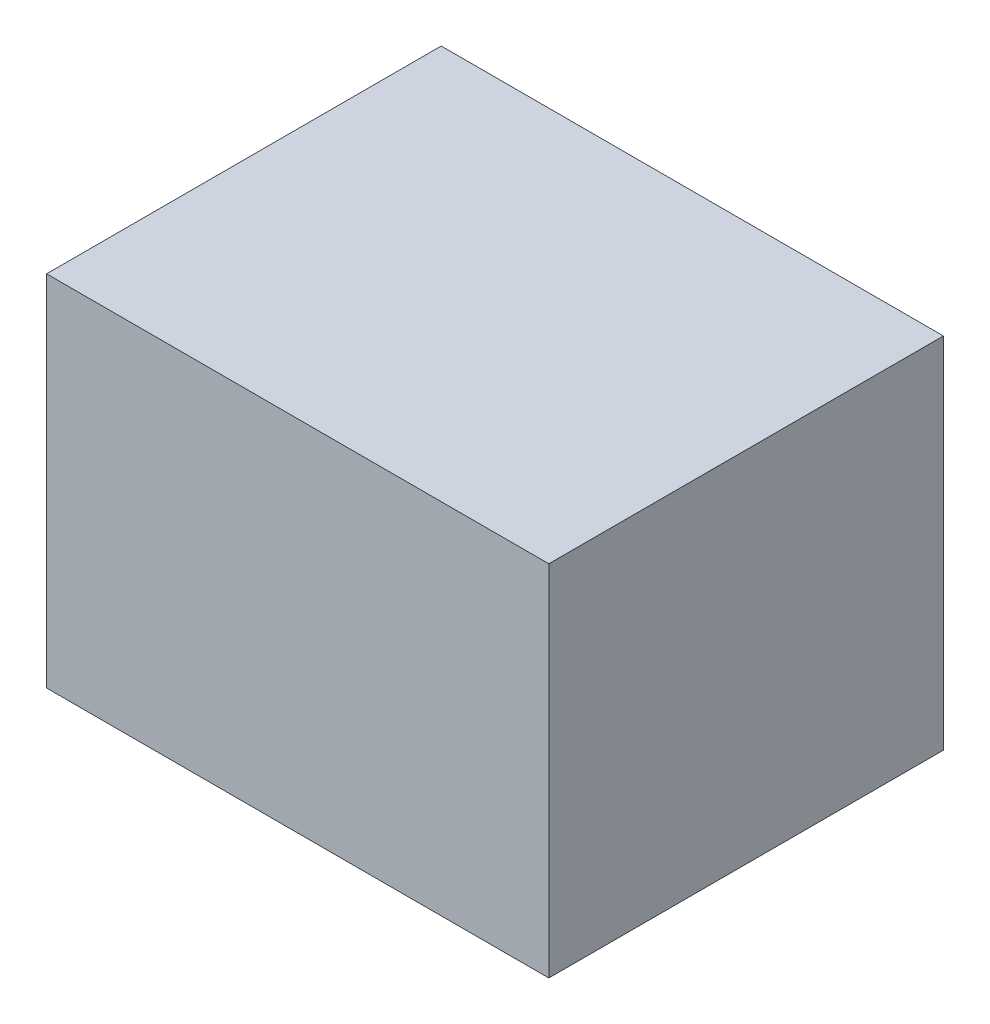
SolidWorks part; units mm, degrees
ref_plane "Front Plane" through (0, 0, 0) normal (0, 0, 1) x (1, 0, 0)
ref_plane "Top Plane" through (0, 0, 0) normal (0, 1, 0) x (1, 0, 0)
ref_plane "Right Plane" through (0, 0, 0) normal (1, 0, 0) x (0, 0, -1)
sketch "Sketch1" plane through (0, 0, 0) normal (0, 1, 0) x (1, 0, 0)
  line L2 (71.12, 55.88) -> (0, 55.88)
  line L3 (71.12, 55.88) -> (71.12, 0)
  line L4 (71.12, 0) -> (0, 0)
  line L5 (0, 55.88) -> (0, 0)
  dimension "D1" = 71.12
  dimension "D2" = 55.88
extrude "Boss-Extrude1" add sketch "Sketch1" along normal blind 50.8
